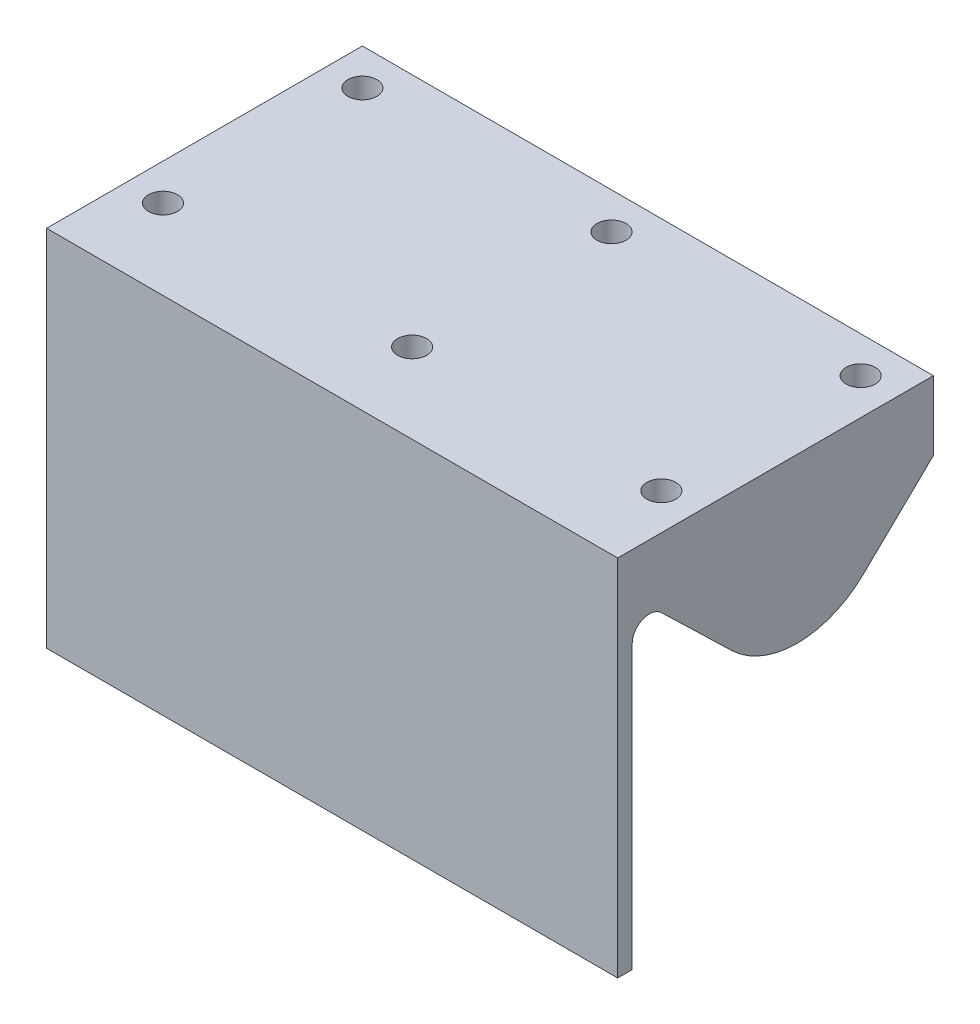
SolidWorks part; units mm, degrees
ref_plane "Front Plane" through (0, 0, 0) normal (0, 0, 1) x (1, 0, 0)
ref_plane "Top Plane" through (0, 0, 0) normal (0, 1, 0) x (1, 0, 0)
ref_plane "Right Plane" through (0, 0, 0) normal (1, 0, 0) x (0, 0, -1)
sketch "Sketch1" plane through (0, 0, 0) normal (0, 1, 0) x (1, 0, 0)
  line L0 (-35.25, 14.7) -> (35.25, -14.7) construction
  line L1 (-35.25, 14.7) -> (35.25, 14.7) construction
  line L2 (-35.25, 14.7) -> (-35.25, -14.7) construction
  line L3 (-35.25, -14.7) -> (35.25, -14.7) construction
  line L4 (35.25, 14.7) -> (35.25, -14.7) construction
  line L5 (-39.25, 0) -> (-35.25, 0) construction
  line L6 (-39.25, 18.7) -> (39.25, 18.7)
  line L7 (-39.25, 18.7) -> (-39.25, -18.7)
  line L8 (-39.25, -18.7) -> (39.25, -18.7)
  line L9 (39.25, 18.7) -> (39.25, -18.7)
  line L10 (35.25, 0) -> (39.25, 0) construction
  line L11 (0, 18.7) -> (0, 14.7) construction
  dimension "D1" = 70.5
  dimension "D2" = 29.4
  dimension "D4" = 4
extrude "Boss-Extrude1" add sketch "Sketch1" along normal blind 9.5
sketch "Sketch6" plane through (0, 9.5, 0) normal (0, 1, 0) x (1, 0, 0)
  line L0 (-34.25, 13.7) -> (0, 13.7) construction
  line L1 (0, 13.7) -> (34.25, 13.7) construction
  line L2 (34.25, 13.7) -> (34.25, -13.7) construction
  line L3 (34.25, -13.7) -> (0, -13.7) construction
  line L4 (0, -13.7) -> (-34.25, -13.7) construction
  line L5 (-34.25, -13.7) -> (-34.25, 13.7) construction
  line L6 (-34.25, 13.7) -> (34.25, -13.7) construction
  line L7 (39.25, 18.7) -> (-39.25, 18.7) construction
  line L8 (0, 13.7) -> (0, 18.7) construction
  line L9 (-34.25, 0) -> (-39.25, 0) construction
  line L10 (-39.25, 18.7) -> (-39.25, -18.7) construction
  circle A0 centre (-34.25, 13.7) radius 2
  circle A1 centre (0, 13.7) radius 2
  circle A2 centre (34.25, 13.7) radius 2
  circle A3 centre (34.25, -13.7) radius 2
  circle A4 centre (0, -13.7) radius 2
  circle A5 centre (-34.25, -13.7) radius 2
  dimension "D1" = 4
  dimension "D2" = 5
extrude "Cut-Extrude1" cut sketch "Sketch6" against normal blind 6.5
sketch "Sketch7" plane through (-39.25, 0, 0) normal (-1, 0, 0) x (0, 0, 1)
  line L1 (-18.7, 0) -> (-9.0374, -9.3448)
  line L2 (-9.0374, -9.3448) -> (9.0374, -9.3448) construction
  line L3 (9.0374, -9.3448) -> (18.7, 0)
  line L6 (-18.7, 0) -> (18.7, 0) construction
  line L7 (-18.7, 0) -> (18.7, 0)
  arc A1 (-9.0374, -9.3448) -> (9.0374, -9.3448) centre (0, 0) ccw
  dimension "D3" = 13
extrude "Boss-Extrude2" add sketch "Sketch7" against normal blind 4
mirror "Mirror1" about plane through (0, 0, 0) normal (1, 0, 0) of "Boss-Extrude2"
sketch "Sketch9" plane through (0, 0, -18.7) normal (0, 0, -1) x (-1, 0, 0)
  line L1 (16.25, 7.5) -> (29.25, 7.5)
  line L2 (16.25, 7.5) -> (16.25, 2)
  line L3 (16.25, 2) -> (29.25, 2)
  line L4 (29.25, 7.5) -> (29.25, 2)
  line L5 (39.25, 9.5) -> (39.25, 0) construction
  line L8 (-39.25, 9.5) -> (39.25, 9.5) construction
  line L9 (22.75, 2) -> (22.75, 0) construction
  line L10 (-35.25, 0) -> (35.25, 0) construction
  line L11 (22.75, 7.5) -> (22.75, 9.5) construction
  line L12 (-16.25, 2) -> (0, 0) construction
  line L13 (-29.25, 7.5) -> (-16.25, 7.5)
  line L14 (-29.25, 7.5) -> (-29.25, 2)
  line L15 (-29.25, 2) -> (-16.25, 2)
  line L16 (-16.25, 7.5) -> (-16.25, 2)
  line L17 (0, 0) -> (16.25, 2) construction
  dimension "D1" = 13
  dimension "D2" = 10
  dimension "D3" = 2
extrude "Cut-Extrude3" cut sketch "Sketch9" against normal through all
sketch "Sketch10" plane through (39.25, 0, 0) normal (1, 0, 0) x (0, 0, -1)
  line L0 (-18.7, 9.5) -> (-18.7, 0) construction
  line L1 (-22.7, -40.5) -> (-24.7, -40.5)
  line L3 (-18.7, 9.5) -> (-24.7, 9.5)
  line L4 (-24.7, -40.5) -> (-24.7, 9.5)
  line L5 (-18.7, 7.5) -> (-12.7, 7.5) construction
  line L6 (-22.7, 3.5) -> (-22.7, -40.5)
  line L7 (-18.7, 9.5) -> (-18.7, 7.5)
  arc A0 (-18.7, 7.5) -> (-22.7, 3.5) centre (-18.7, 3.5) ccw
  dimension "D1" = 2
  dimension "D2" = 50
  dimension "D3" = 4
extrude "Boss-Extrude3" add sketch "Sketch10" against normal up to surface (78.5 mm away) up to face at (-39.25, -0.5575, 0)
sketch "Sketch11" plane through (-39.25, 0, 0) normal (-1, 0, 0) x (0, 0, 1)
  line L0 (22.7, 3.5) -> (22.7, -40.5) construction
  line L1 (9.0374, -9.3448) -> (18.7, 0) construction
  line L2 (18.7, 7.5) -> (18.7, 0) construction
  line L3 (18.7, 7.5) -> (18.7, 0)
  line L4 (22.7, 3.5) -> (22.7, -1.6962)
  arc A0 (18.7, 0) -> (22.7, -1.6962) centre (20.3404, -1.6962) cw
  arc A1 (22.7, 3.5) -> (18.7, 7.5) centre (18.7, 3.5) ccw construction
  arc A2 (22.7, 3.5) -> (18.7, 7.5) centre (18.7, 3.5) ccw
extrude "Boss-Extrude4" add sketch "Sketch11" against normal up to surface (4 mm away) up to face at (-35.25, -5.5862, 0)
sketch "Sketch12" plane through (39.25, 0, 0) normal (1, 0, 0) x (0, 0, -1)
  line L2 (-18.7, 0) -> (-18.7, 7.5)
  line L3 (-22.7, 3.5) -> (-22.7, -1.6962)
  line L4 (-18.7, 0) -> (-18.7, 7.5)
  line L5 (-22.7, 3.5) -> (-22.7, -1.6962)
  arc A2 (-18.7, 0) -> (-22.7, -1.6962) centre (-20.3404, -1.6962) ccw
  arc A3 (-18.7, 7.5) -> (-22.7, 3.5) centre (-18.7, 3.5) ccw
  arc A4 (-18.7, 0) -> (-22.7, -1.6962) centre (-20.3404, -1.6962) ccw
  arc A5 (-18.7, 7.5) -> (-22.7, 3.5) centre (-18.7, 3.5) ccw
  dimension "D1" = 0
extrude "Boss-Extrude5" add sketch "Sketch12" against normal up to surface (4 mm away) up to face at (35.25, -5.5862, 0)
